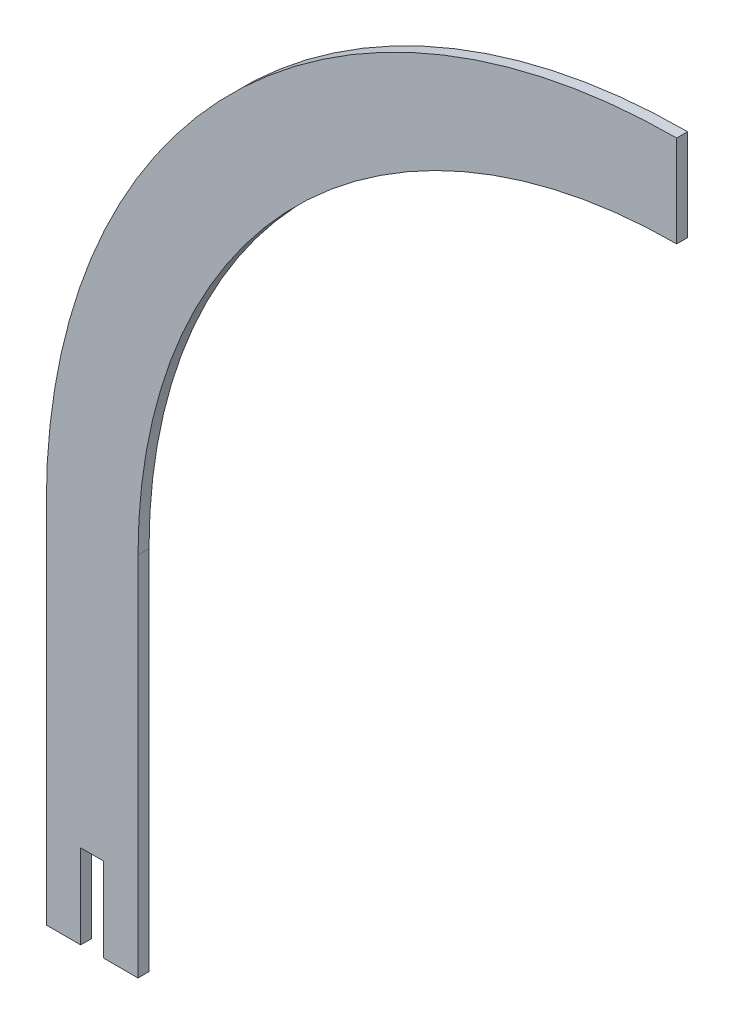
SolidWorks part; units mm, degrees
material "Pine"
ref_plane "Front Plane" through (0, 0, 0) normal (0, 0, 1) x (1, 0, 0)
ref_plane "Top Plane" through (0, 0, 0) normal (0, 1, 0) x (1, 0, 0)
ref_plane "Right Plane" through (0, 0, 0) normal (1, 0, 0) x (0, 0, -1)
sketch "Sketch1" plane through (0, 0, 0) normal (0, 0, 1) x (1, 0, 0)
  line L0 (-1416.0651, 421.5375) -> (-1416.0651, -188.0625)
  line L1 (-1416.0651, -188.0625) -> (-1358.9151, -188.0625)
  line L2 (-1263.6651, -188.0625) -> (-1263.6651, 420.9101)
  line L3 (-368.3151, 1468.6601) -> (-368.3151, 1316.2601)
  line L4 (-1339.8651, -48.3625) -> (-1339.8651, 119.3845) construction
  line L5 (-1320.8151, -188.0625) -> (-1263.6651, -188.0625)
  line L6 (-1358.9151, -48.3625) -> (-1320.8151, -48.3625)
  line L7 (-1358.9151, -48.3625) -> (-1358.9151, -188.0625)
  line L9 (-1320.8151, -48.3625) -> (-1320.8151, -188.0625)
  arc A1 (-368.3151, 1468.6601) -> (-1416.0651, 420.9101) centre (-368.3151, 420.9101) ccw
  arc A2 (-368.3151, 1316.2601) -> (-1263.6651, 420.9101) centre (-368.3151, 420.9101) ccw
  dimension "D1" = 38.1
  dimension "D3" = 1790.7
  dimension "D4" = 2095.5
  dimension "D5" = 152.4
  dimension "D2" = 609.6
  dimension "D6" = 139.7
  dimension "D7" = 19.05
extrude "Boss-Extrude1" add sketch "Sketch1" along normal blind 18.2562
